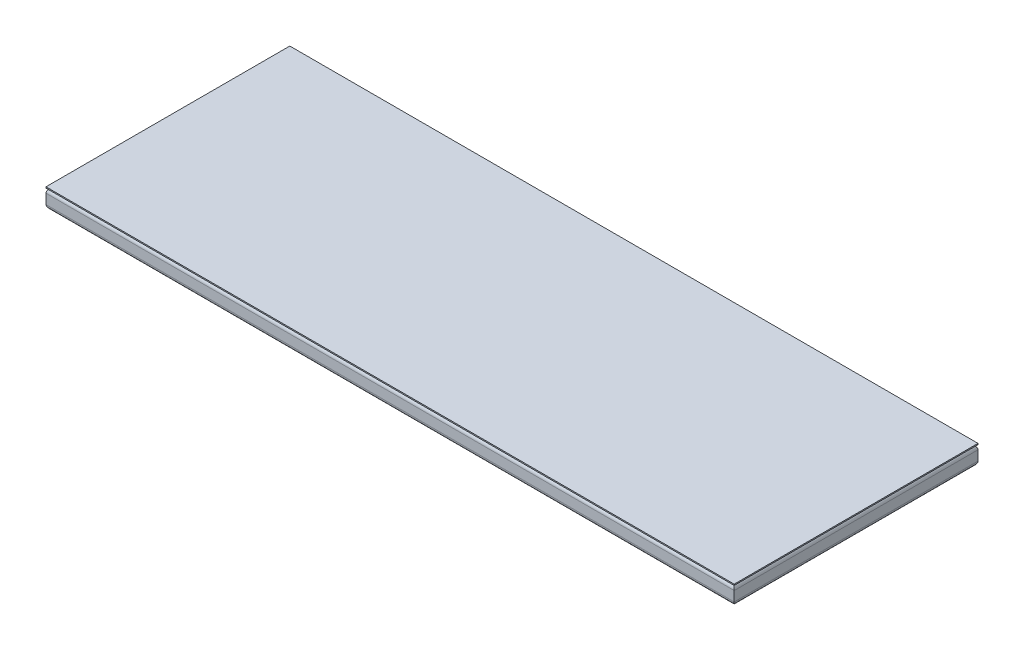
SolidWorks part; units mm, degrees
ref_plane "Alzado" through (0, 0, 0) normal (0, 0, 1) x (1, 0, 0)
ref_plane "Planta" through (0, 0, 0) normal (0, 1, 0) x (1, 0, 0)
ref_plane "Vista lateral" through (0, 0, 0) normal (1, 0, 0) x (0, 0, -1)
sketch "Croquis1" plane through (0, 0, 0) normal (0, 1, 0) x (1, 0, 0)
  line L1 (-470, 166.5) -> (470, 166.5)
  line L2 (-470, 166.5) -> (-470, -166.5)
  line L3 (-470, -166.5) -> (470, -166.5)
  line L4 (470, 166.5) -> (470, -166.5)
  line L5 (-470, 166.5) -> (470, -166.5) construction
  line L6 (-470, -166.5) -> (470, 166.5) construction
  point P0 (0, 0)
  dimension "D1" = 940
  dimension "D2" = 333
other "Tubo cuadrado 2 X 2 X 0.25(1)"
ref_plane "Plano1" through (457.3, -12.7, -166.5) normal (0, 0, 1) x (1, 0, 0)
sketch "Sketch1" plane through (457.3, -12.7, -166.5) normal (0, 0, 1) x (1, 0, 0)
  line L0 (-6.7, -9.7) -> (6.7, -9.7)
  line L1 (-9.7, -6.7) -> (-9.7, 6.7)
  line L2 (6.7, 9.7) -> (-6.7, 9.7)
  line L3 (9.7, 6.7) -> (9.7, -6.7)
  line L4 (-6.7, -12.7) -> (6.7, -12.7)
  line L5 (-12.7, -6.7) -> (-12.7, 6.7)
  line L6 (6.7, 12.7) -> (-6.7, 12.7)
  line L7 (12.7, 6.7) -> (12.7, -6.7)
  line L8 (0, 0) -> (9.7, 0) construction
  line L9 (0, 0) -> (0, 9.7) construction
  arc A0 (12.7, 6.7) -> (6.7, 12.7) centre (6.7, 6.7) ccw
  arc A1 (6.7, -12.7) -> (12.7, -6.7) centre (6.7, -6.7) ccw
  arc A2 (-12.7, -6.7) -> (-6.7, -12.7) centre (-6.7, -6.7) ccw
  arc A3 (-6.7, 12.7) -> (-12.7, 6.7) centre (-6.7, 6.7) ccw
  arc A4 (-6.7, 9.7) -> (-9.7, 6.7) centre (-6.7, 6.7) ccw
  arc A5 (9.7, 6.7) -> (6.7, 9.7) centre (6.7, 6.7) ccw
  arc A6 (6.7, -9.7) -> (9.7, -6.7) centre (6.7, -6.7) ccw
  arc A7 (-9.7, -6.7) -> (-6.7, -9.7) centre (-6.7, -6.7) ccw
  point P3 (0, 12.7)
  point P4 (12.7, 0)
  point P5 (0, -12.7)
  point P6 (-12.7, 0)
  point P7 (-12.7, 12.7)
  point P8 (-12.7, -12.7)
  point P33 (0, 0)
  point P35 (12.7, -12.7)
  point P36 (12.7, 12.7)
  point P37 (0, 0)
  dimension "D1" = 6
  dimension "Thickness" = 3
  dimension "V_leg" = 25.4
sketch "Croquis3" plane through (0, 0, 0) normal (0, 1, 0) x (1, 0, 0)
  line L7 (470, 166.5) -> (-470, 166.5)
  line L8 (470, 166.5) -> (470, -166.5)
  line L9 (470, -166.5) -> (-470, -166.5)
  line L10 (-470, 166.5) -> (-470, -166.5)
  line L11 (470, 166.5) -> (-470, -166.5) construction
  line L12 (470, -166.5) -> (-470, 166.5) construction
  point P0 (0, 0)
extrude "Saliente-Extruir2" add sketch "Croquis3" along normal blind 1.62 separate body
